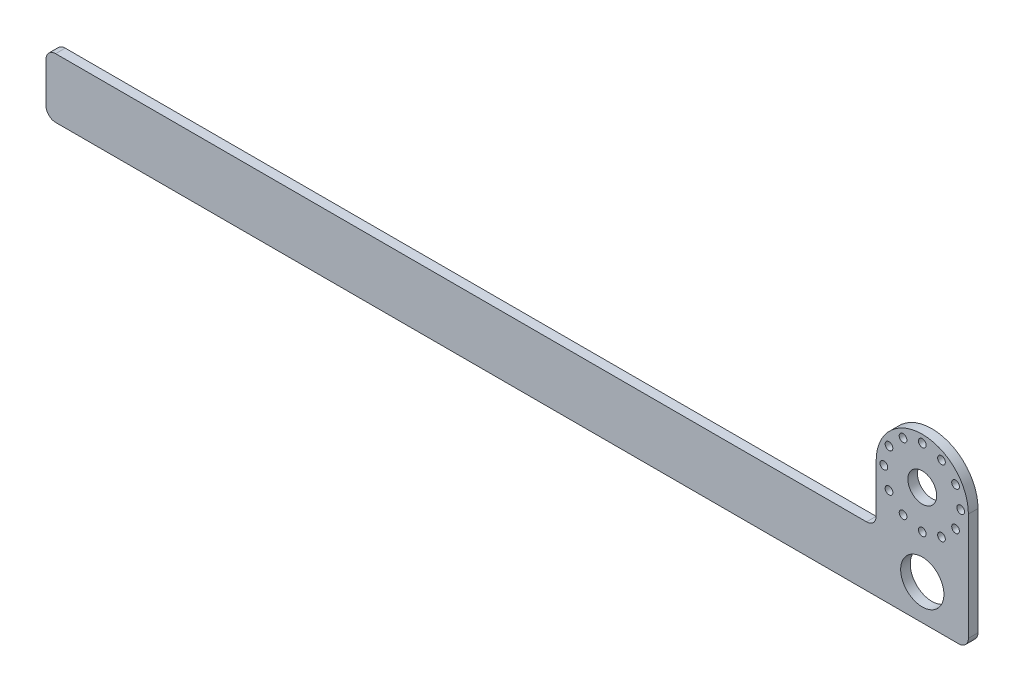
SolidWorks part; units mm, degrees
material "PC High Viscosity"
ref_plane "Front Plane" through (0, 0, 0) normal (0, 0, 1) x (1, 0, 0)
ref_plane "Top Plane" through (0, 0, 0) normal (0, 1, 0) x (1, 0, 0)
ref_plane "Right Plane" through (0, 0, 0) normal (1, 0, 0) x (0, 0, -1)
sketch "Sketch1" plane through (0, 0, 0) normal (0, 0, 1) x (1, 0, 0)
  line L2 (0, 0) -> (0, 39.37)
  line L3 (0, 39.37) -> (40.5308, 39.37)
  line L8 (40.5308, 39.37) -> (548.64, 39.37)
  line L9 (0, 0) -> (609.6, 0)
  line L19 (590.55, 0) -> (590.55, 10.0162) construction
  line L20 (590.55, 10.0162) -> (76.2, 10.0162) construction
  line L21 (76.2, 10.0162) -> (76.2, 0) construction
  line L22 (609.6, 77.47) -> (609.6, 0)
  line L27 (548.64, 77.47) -> (548.64, 39.37)
  line L28 (560.3214, 26.7503) -> (569.7207, 79.1558) construction
  line L29 (588.5193, 79.1558) -> (597.9186, 26.7503) construction
  circle A1 centre (579.12, 77.47) radius 9.525
  circle A2 centre (579.12, 77.47) radius 25.4 construction
  circle A3 centre (579.12, 102.87) radius 2.54
  circle A4 centre (591.82, 99.467) radius 2.54
  circle A5 centre (601.117, 90.17) radius 2.54
  circle A6 centre (604.52, 77.47) radius 2.54
  circle A7 centre (601.117, 64.77) radius 2.54
  circle A8 centre (591.82, 55.473) radius 2.54
  circle A9 centre (579.12, 52.07) radius 2.54
  circle A10 centre (566.42, 55.473) radius 2.54
  circle A11 centre (557.123, 64.77) radius 2.54
  circle A12 centre (553.72, 77.47) radius 2.54
  circle A13 centre (557.123, 90.17) radius 2.54
  circle A14 centre (566.42, 99.467) radius 2.54
  arc A15 (609.6, 77.47) -> (548.64, 77.47) centre (579.12, 77.47) ccw
  circle A16 centre (557.123, 90.17) radius 5.08 construction
  arc A17 (588.5193, 79.1558) -> (569.7207, 79.1558) centre (579.12, 77.47) ccw construction
  arc A18 (560.3214, 26.7503) -> (597.9186, 26.7503) centre (579.12, 23.3786) ccw construction
  circle A19 centre (579.12, 23.3786) radius 14.2875
  point P48 (579.12, 77.47)
  dimension "D3" = 5.08
  dimension "D4" = 50.8
  dimension "D9" = 10.16
  dimension "D5" = 19.05
  dimension "D12" = 28.575
  dimension "D2" = 39.37
  dimension "D1" = 609.6
  dimension "D8" = 38.1
  dimension "D7" = 38.1
  dimension "D6" = 12
extrude "Boss-Extrude1" add sketch "Sketch1" along normal blind 6.35
fillet "Fillet2" radius 6.35 4 edges at (0, 39.37, 3.175) (0, 0, 3.175) (548.64, 39.37, 3.175) (609.6, 0, 3.175)
sketch "Sketch2" plane through (0, 0, 6.35) normal (0, 0, 1) x (1, 0, 0)
  line L0 (558.8, 0) -> (43.7057, 0)
  line L1 (43.7057, 0) -> (43.7057, 5.715)
  line L2 (43.7057, 5.715) -> (558.8, 5.715)
  line L3 (558.8, 5.715) -> (558.8, 0)
  line L5 (557.8755, 2.54) -> (549.711, 2.54) construction
  line L6 (558.8, 0) -> (556.7199, 5.715)
  line L7 (609.6, 77.47) -> (609.6, 6.35) construction
  line L8 (552.8688, 0) -> (558.8, 0)
  line L10 (556.7199, 5.715) -> (554.9488, 5.715)
  line L11 (558.8, 0) -> (552.8688, 0)
  line L12 (552.8688, 0) -> (554.9488, 5.715)
  line L13 (554.9488, 5.715) -> (556.7199, 5.715)
  line L14 (558.8, 0) -> (552.8688, 0)
  line L15 (554.9488, 5.715) -> (556.7199, 5.715)
  line L16 (558.8, 0) -> (552.8688, 0)
  line L17 (552.8688, 0) -> (558.8, 0)
  line L19 (556.7199, 5.715) -> (554.9488, 5.715) construction
  line L20 (552.8688, 0) -> (558.8, 0) construction
  line L23 (0, 0) -> (609.6, 0) construction
  point P8 (553.7932, 2.54)
  point P16 (557.8755, 2.54)
  dimension "D1" = 70
  dimension "D2" = 2.54
  dimension "D3" = 3.175
  dimension "D4" = 70
  dimension "D5" = 1.7711
  dimension "D6" = 50.8
  dimension "D7" = 515.0943
equation "\"D11@Sketch1\"=(24*5mm)/pi"
equation "\"D10@Sketch1\"=(12*5mm)/pi"
equation "\"D13@Sketch1\"=(40*5mm)-0.005"
